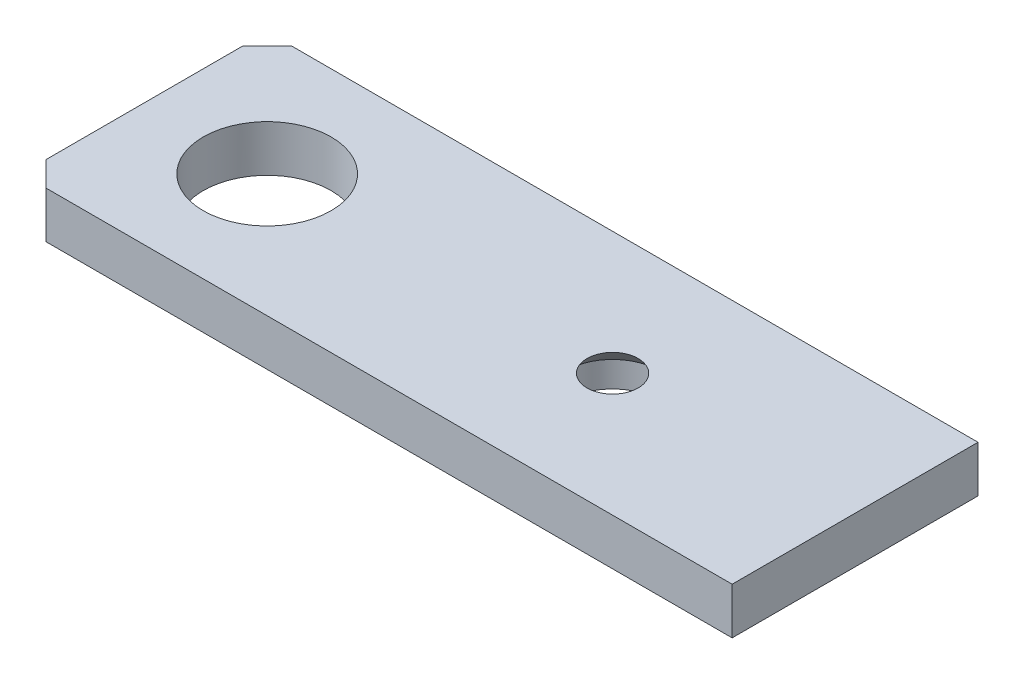
SolidWorks part; units mm, degrees
ref_plane "Front Plane" through (0, 0, 0) normal (0, 0, 1) x (1, 0, 0)
ref_plane "Top Plane" through (0, 0, 0) normal (0, 1, 0) x (1, 0, 0)
ref_plane "Right Plane" through (0, 0, 0) normal (1, 0, 0) x (0, 0, -1)
sketch "Sketch1" plane through (0, 0, 0) normal (0, 1, 0) x (1, 0, 0)
  line L1 (21.15, -21.15) -> (-21.15, -21.15)
  line L2 (21.15, -21.15) -> (21.15, 21.15)
  line L3 (21.15, 21.15) -> (-21.15, 21.15)
  line L4 (-21.15, -21.15) -> (-21.15, 21.15)
  line L5 (21.15, -21.15) -> (-21.15, 21.15) construction
  line L6 (21.15, 21.15) -> (-21.15, -21.15) construction
  circle A0 centre (0, 0) radius 11
  dimension "D1" = 22
  dimension "D2" = 42.3
  dimension "D3" = 42.3
extrude "Boss-Extrude1" add sketch "Sketch1" along normal blind 2
sketch "Sketch2" plane through (0, 2, 0) normal (0, 1, 0) x (1, 0, 0)
  line L0 (21.15, 21.15) -> (21.15, -21.15)
  line L1 (21.15, -21.15) -> (101.15, -21.15)
  line L2 (101.15, -21.15) -> (101.15, 21.15)
  line L3 (101.15, 21.15) -> (21.15, 21.15)
  circle A0 centre (59.43, 0) radius 8
  dimension "D1" = 16
  dimension "D2" = 59.43
  dimension "D3" = 80
extrude "Boss-Extrude2" add sketch "Sketch2" against normal blind 2
sketch "Sketch3" plane through (0, 0, 0) normal (0, -1, 0) x (1, 0, 0)
  line L4 (-21.15, 21.15) -> (-21.15, -21.15)
  line L5 (-21.15, -21.15) -> (101.15, -21.15)
  line L6 (101.15, -21.15) -> (101.15, 21.15)
  line L7 (101.15, 21.15) -> (-21.15, 21.15)
  line L8 (-21.15, 21.15) -> (-21.15, -21.15)
  line L9 (-21.15, -21.15) -> (101.15, -21.15)
  line L10 (101.15, -21.15) -> (101.15, 21.15)
  line L11 (101.15, 21.15) -> (-21.15, 21.15)
  circle A0 centre (59.43, 0) radius 8 construction
  circle A1 centre (0, 0) radius 11 construction
  circle A2 centre (59.43, 0) radius 8
  circle A3 centre (0, 0) radius 11
  dimension "D1" = 0
extrude "Boss-Extrude3" add sketch "Sketch3" along normal blind 6
sketch "Sketch5" plane through (0, 0, 0) normal (0, 0, 1) x (1, 0, 0)
  line L0 (67.43, 2) -> (63.83, 2)
  line L1 (63.83, 2) -> (67.43, -1.6)
  line L2 (67.43, -1.6) -> (67.43, 2)
  dimension "D1" = 3.6
  dimension "D2" = 45
revolve "Revolve1" add sketch "Sketch5" angle 360 about axis through (59.43, 0, 0) along (0, 1, 0)
sketch "Sketch6" plane through (0, 2, 0) normal (0, 1, 0) x (1, 0, 0)
  line L0 (-21.15, 16.9074) -> (-16.9074, 21.15)
  line L1 (-21.15, 21.15) -> (-21.15, -21.15) construction
  line L2 (101.15, 21.15) -> (-21.15, 21.15) construction
  line L3 (-16.9074, 21.15) -> (-21.15, 21.15)
  line L4 (-21.15, 21.15) -> (-21.15, 16.9074)
  line L5 (-21.15, -21.15) -> (-21.15, -16.9074)
  line L6 (-21.15, -16.9074) -> (-16.9074, -21.15)
  line L7 (-21.15, -21.15) -> (101.15, -21.15) construction
  line L8 (-16.9074, -21.15) -> (-21.15, -21.15)
  point P11 (-21.15, 16.9074)
  point P15 (-17.5063, 21.15)
  dimension "D2" = 6
extrude "Cut-Extrude1" cut sketch "Sketch6" against normal up to surface (8 mm away) up to face at (59.43, -6, -8)
